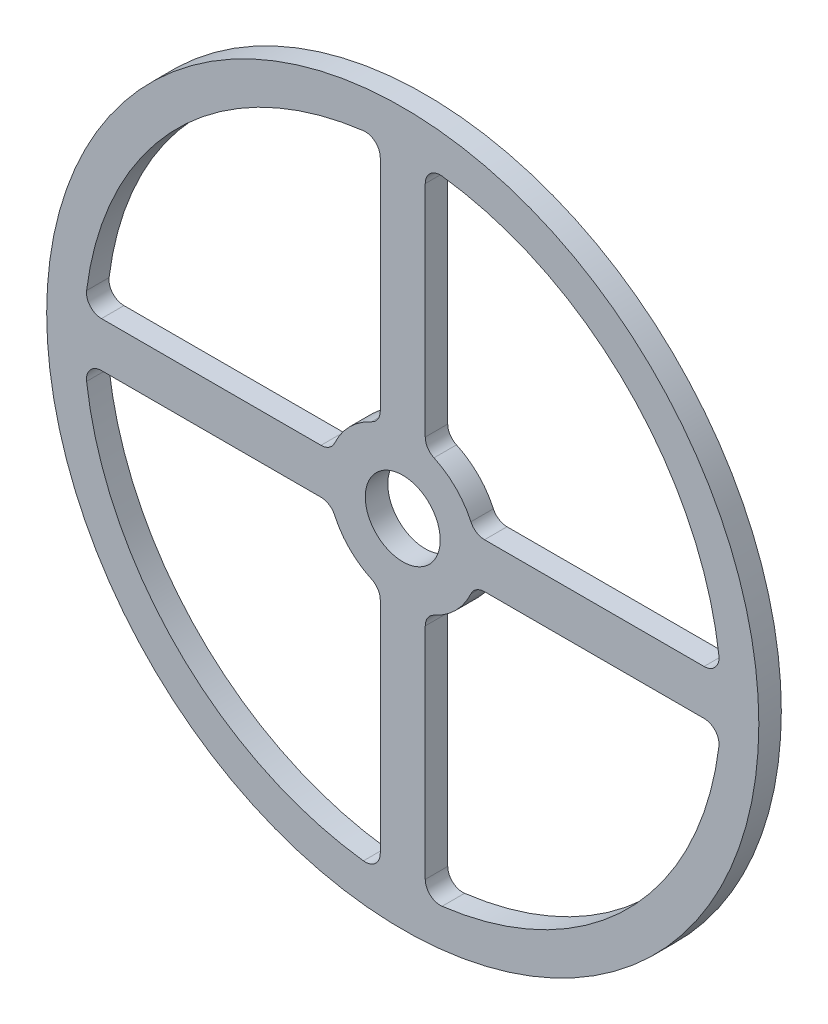
SolidWorks part; units mm, degrees
ref_plane "前视基准面" through (0, 0, 0) normal (0, 0, 1) x (1, 0, 0)
ref_plane "上视基准面" through (0, 0, 0) normal (0, 1, 0) x (1, 0, 0)
ref_plane "右视基准面" through (0, 0, 0) normal (1, 0, 0) x (0, 0, -1)
sketch "草图1" plane through (0, 0, 0) normal (0, 0, 1) x (1, 0, 0)
  line L0 (3, 42.394) -> (3, 9.5394)
  line L1 (9.5394, 3) -> (42.394, 3)
  line L2 (0, 72.2615) -> (0, -79.5295) construction
  line L3 (-78.2791, 0) -> (88.2263, 0) construction
  line L4 (-9.5394, -3) -> (-42.394, -3)
  line L5 (9.5394, -3) -> (42.394, -3)
  line L7 (-3, 9.5394) -> (-3, 42.394)
  line L8 (-3, -9.5394) -> (-3, -42.394)
  line L9 (3, -9.5394) -> (3, -42.394)
  line L10 (-9.5394, 3) -> (-42.394, 3)
  circle A0 centre (0, 0) radius 47.5
  arc A1 (-3, 42.394) -> (-42.394, 3) centre (0, 0) ccw
  arc A2 (3, -42.394) -> (42.394, -3) centre (0, 0) ccw
  arc A3 (-42.394, -3) -> (-3, -42.394) centre (0, 0) ccw
  arc A4 (42.394, 3) -> (3, 42.394) centre (0, 0) ccw
  arc A5 (-3, 9.5394) -> (-9.5394, 3) centre (0, 0) ccw
  circle A6 centre (0, 0) radius 5
  arc A7 (9.5394, 3) -> (3, 9.5394) centre (0, 0) ccw
  arc A8 (-9.5394, -3) -> (-3, -9.5394) centre (0, 0) ccw
  arc A9 (3, -9.5394) -> (9.5394, -3) centre (0, 0) ccw
  dimension "D1" = 95
  dimension "D2" = 85
  dimension "D5" = 10
  dimension "D6" = 20
  dimension "D3" = 3
  dimension "D4" = 3
extrude "凸台-拉伸1" add sketch "草图1" along normal blind 3
fillet "圆角1" radius 2 1 edges at (3, 42.394, 1.5)
fillet "圆角2" radius 2 7 edges at (42.394, 3, 1.5) (42.394, -3, 1.5) (3, -42.394, 1.5) (-3, -42.394, 1.5) (-42.394, -3, 1.5) (-42.394, 3, 1.5) (-3, 42.394, 1.5)
fillet "圆角4" radius 2 8 edges at (3, -9.5394, 1.5) (-3, -9.5394, 1.5) (-9.5394, -3, 1.5) (-9.5394, 3, 1.5) (-3, 9.5394, 1.5) (3, 9.5394, 1.5) (9.5394, 3, 1.5) (9.5394, -3, 1.5)
